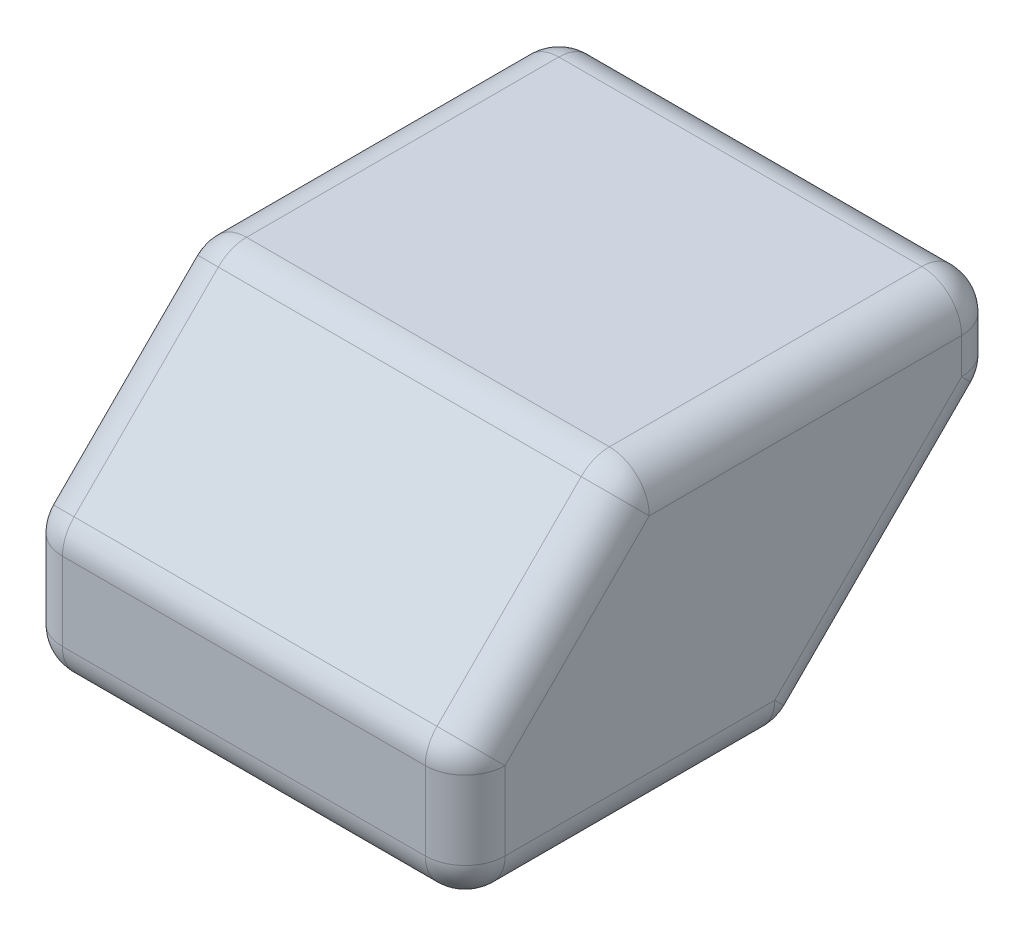
SolidWorks part; units mm, degrees
ref_plane "Front Plane" through (0, 0, 0) normal (0, 0, 1) x (1, 0, 0)
ref_plane "Top Plane" through (0, 0, 0) normal (0, 1, 0) x (1, 0, 0)
ref_plane "Right Plane" through (0, 0, 0) normal (1, 0, 0) x (0, 0, -1)
sketch "Sketch1" plane through (0, 0, 0) normal (0, 1, 0) x (1, 0, 0)
  line L1 (0, 0) -> (26.416, 0)
  line L2 (0, 0) -> (0, 32.004)
  line L3 (0, 32.004) -> (26.416, 32.004)
  line L4 (26.416, 0) -> (26.416, 32.004)
  dimension "D1" = 26.416
  dimension "D2" = 32.004
extrude "Boss-Extrude1" add sketch "Sketch1" along normal blind 18.034
chamfer "Chamfer1" distance 12.54 angle 45 1 edges at (13.208, 0, -32.004)
chamfer "Chamfer2" distance 10 angle 45 1 edges at (13.208, 18.034, 0)
fillet "Fillet1" radius 2.38 18 edges at (0, 13.034, -5) (13.208, 8.034, 0) (26.416, 13.034, -5) (13.208, 18.034, -10) (26.416, 6.27, -25.734) (13.208, 0, -19.464) (0, 6.27, -25.734) (13.208, 12.54, -32.004) (0, 4.017, 0) (26.416, 4.017, 0) (26.416, 15.287, -32.004) (0, 15.287, -32.004) (13.208, 18.034, -32.004) (26.416, 18.034, -21.002) (0, 18.034, -21.002) (26.416, 0, -9.732) (13.208, 0, 0) (0, 0, -9.732)
